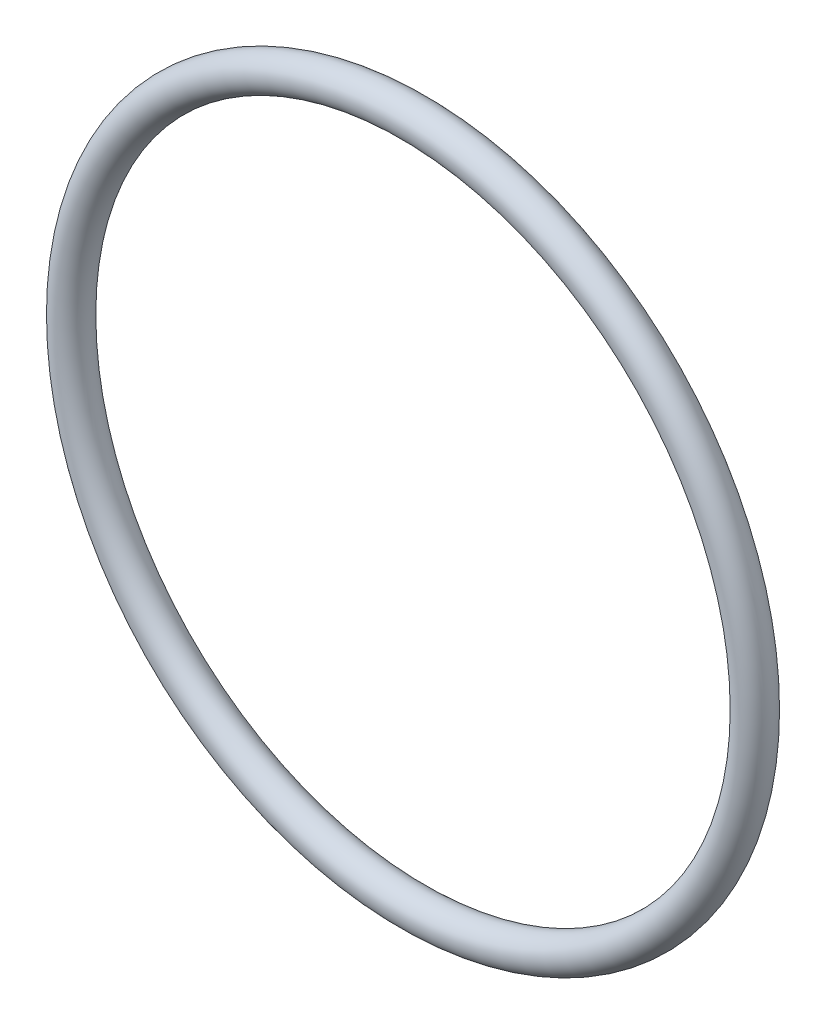
SolidWorks part; units mm, degrees
ref_plane "Front" through (0, 0, 0) normal (0, 0, 1) x (1, 0, 0)
ref_plane "Top" through (0, 0, 0) normal (0, 1, 0) x (1, 0, 0)
ref_plane "Right" through (0, 0, 0) normal (1, 0, 0) x (0, 0, -1)
sketch "Sketch1" plane through (0, 0, 0) normal (1, 0, 0) x (0, -1, 0)
  line L0 (0, -0.889) -> (0, 0.889) construction
  line L2 (-20.1308, 0) -> (20.1308, 0) construction
  line L3 (-16.5227, 0) -> (16.5227, 0) construction
  circle A0 centre (17.4117, 0) radius 0.889
  point P9 (16.5227, 0)
  point P10 (18.3007, 0)
  point P13 (17.4117, 0.889)
  point P14 (17.4117, -0.889)
  dimension "Width" = 1.778
  dimension "ID" = 33.0454
revolve "Revolve1" add sketch "Sketch1" angle 360 about L0
